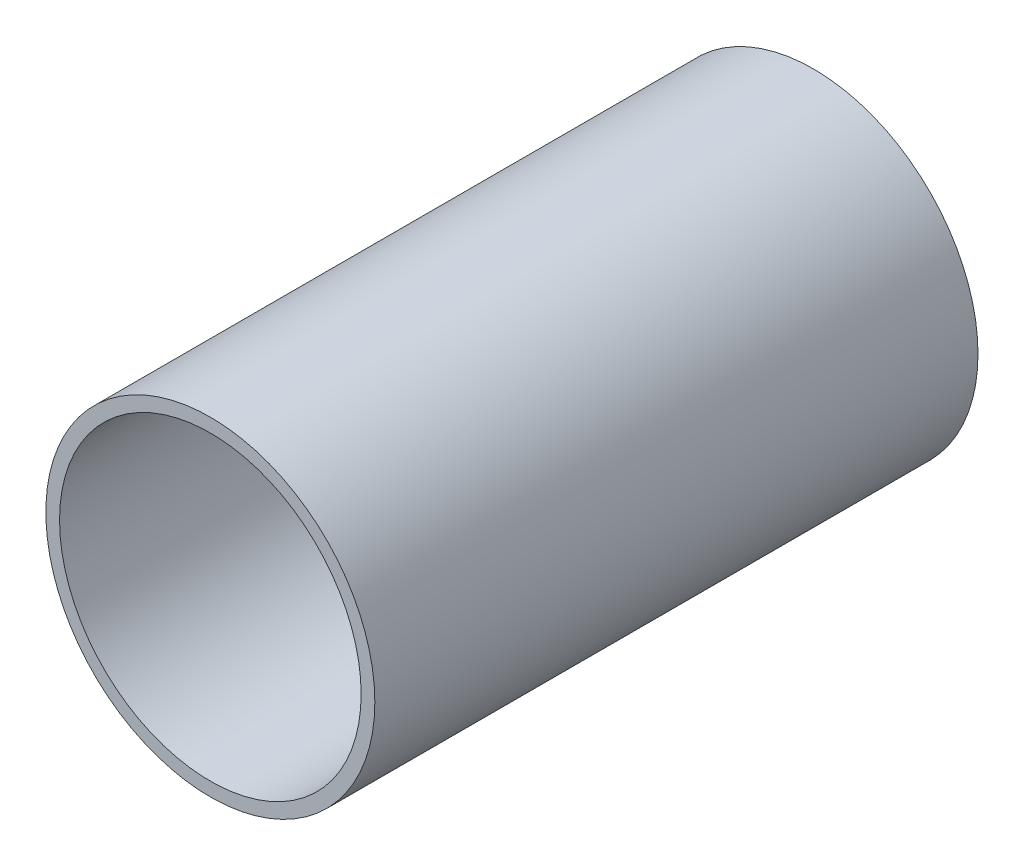
SolidWorks part; units mm, degrees
ref_plane "Front Plane" through (0, 0, 0) normal (0, 0, 1) x (1, 0, 0)
ref_plane "Top Plane" through (0, 0, 0) normal (0, 1, 0) x (1, 0, 0)
ref_plane "Right Plane" through (0, 0, 0) normal (1, 0, 0) x (0, 0, -1)
sketch "Sketch1" plane through (0, 0, 0) normal (0, 0, 1) x (1, 0, 0)
  circle A0 centre (0, 0) radius 34.925
  circle A1 centre (0, 0) radius 38.1
extrude "Boss-Extrude1" add sketch "Sketch1" along normal blind 139.7
